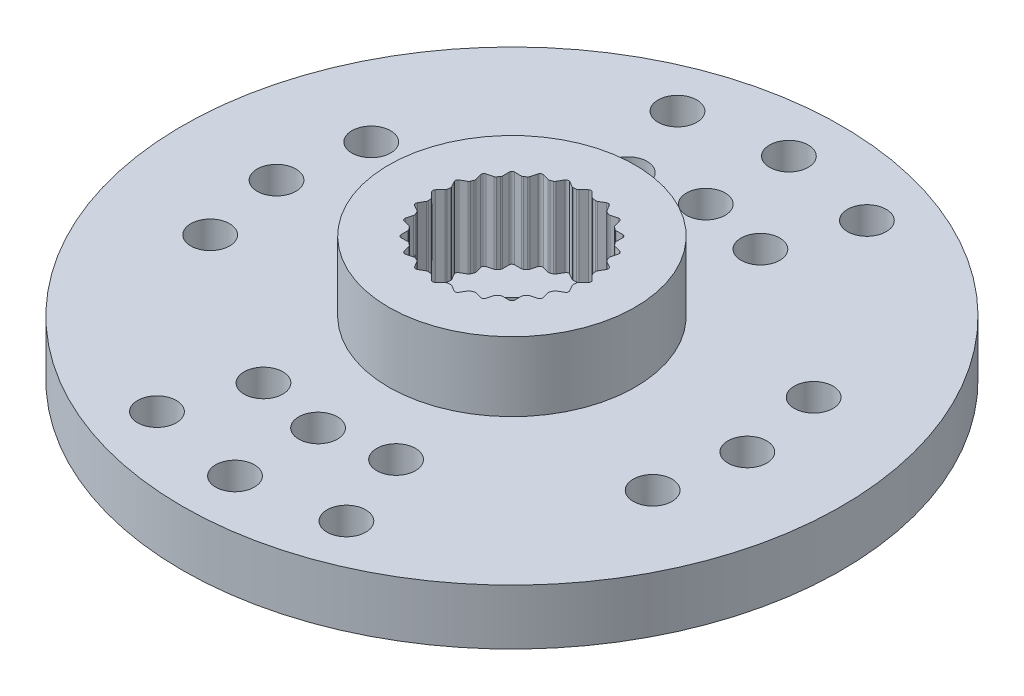
SolidWorks part; units mm, degrees
ref_plane "Спереди" through (0, 0, 0) normal (0, 0, 1) x (1, 0, 0)
ref_plane "Сверху" through (0, 0, 0) normal (0, 1, 0) x (1, 0, 0)
ref_plane "Справа" through (0, 0, 0) normal (1, 0, 0) x (0, 0, -1)
sketch "Эскиз1" plane through (0, 0, 0) normal (0, 1, 0) x (1, 0, 0)
  circle A0 centre (0, 0) radius 11.9
  dimension "D1" = 23.8
extrude "Бобышка-Вытянуть1" add sketch "Эскиз1" along normal blind 2
sketch "Эскиз2" plane through (0, 2, 0) normal (0, 1, 0) x (1, 0, 0)
  circle A0 centre (0, 0) radius 4.45
  dimension "D1" = 8.9
extrude "Бобышка-Вытянуть2" add sketch "Эскиз2" along normal blind 2.5
sketch "Эскиз3" plane through (0, 0, 0) normal (0, -1, 0) x (1, 0, 0)
  circle A0 centre (0, 0) radius 3.75
  dimension "D1" = 7.5
extrude "Бобышка-Вытянуть3" add sketch "Эскиз3" along normal blind 0.5
sketch "Эскиз4" plane through (0, -0.5, 0) normal (0, -1, 0) x (1, 0, 0)
  circle A0 centre (0, 0) radius 3
  dimension "D1" = 6
extrude "Вырез-Вытянуть1" cut sketch "Эскиз4" against normal blind 1
sketch "Эскиз5" plane through (0, 0.5, 0) normal (0, -1, 0) x (1, 0, 0)
  circle A0 centre (0, 0) radius 1.4
  dimension "D1" = 2.8
extrude "Вырез-Вытянуть2" cut sketch "Эскиз5" against normal through all
sketch "Эскиз6" plane through (0, 4.5, 0) normal (0, 1, 0) x (1, 0, 0)
  circle A0 centre (0, 0) radius 2.65
  dimension "D1" = 5.3
extrude "Вырез-Вытянуть3" cut sketch "Эскиз6" against normal blind 2.9
sketch "Эскиз7" plane through (0, 4.5, 0) normal (0, 1, 0) x (1, 0, 0)
  line L0 (0, 2.9) -> (-0.2631, 2.6369)
  line L1 (0, 2.9) -> (0.2631, 2.6369)
  line L2 (0, 2.9) -> (0, 0) construction
  circle A0 centre (0, 0) radius 2.65 construction
  arc A1 (-0.2631, 2.6369) -> (0.2631, 2.6369) centre (0, 0) cw
  circle A2 centre (0, 0) radius 2.65 construction
  circle A3 centre (0, 0) radius 2.9 construction
  dimension "D3" = 5.8
  dimension "D1" = 90
  dimension "D2" = 45
extrude "Вырез-Вытянуть4" cut sketch "Эскиз7" against normal up to surface (2.9 mm away) up to face at (0, 1.6, 2.65)
fillet "Скругление1" radius 0.1 3 edges at (0.2631, 3.05, -2.6369) (-0.2631, 3.05, -2.6369) (0, 3.05, -2.9)
pattern_circular "Круговой массив1" count 24 over 360 about axis through (0, 0, 0) along (0, 1, 0) of "Вырез-Вытянуть4", "Скругление1"
sketch "Эскиз8" plane through (0, 0, 0) normal (0, -1, 0) x (1, 0, 0)
  line L0 (0, 0) -> (0, 7) construction
  line L1 (0, 7) -> (0, 10) construction
  circle A0 centre (0, 0) radius 7 construction
  circle A1 centre (0, 0) radius 10 construction
  circle A2 centre (0, 10) radius 0.7
  circle A3 centre (0, 7) radius 0.7
  dimension "D1" = 20
  dimension "D2" = 14
  dimension "D3" = 1.4
extrude "Вырез-Вытянуть5" cut sketch "Эскиз8" against normal through all
pattern_circular "Круговой массив2" count 18 over 360 about axis through (0, 0, 0) along (0, 1, 0) skipping 2, 3, 4, 5, 6, 7, 11, 12, 13, 14, 15, 16 of "Вырез-Вытянуть5"
sketch "Эскиз10" plane through (0, 0, 0) normal (0, -1, 0) x (1, 0, 0)
  circle A0 centre (0, 0) radius 8.5 construction
  circle A1 centre (8.5, 0) radius 0.7
  circle A2 centre (0, 10) radius 0.7 construction
  dimension "D1" = 17
extrude "Вырез-Вытянуть6" cut sketch "Эскиз10" against normal through all
pattern_circular "Круговой массив3" count 18 over 360 about axis through (0, 0, 0) along (0, 1, 0) skipping 2, 3, 4, 5, 6, 7, 11, 12, 13, 14, 15, 16 of "Вырез-Вытянуть6"
